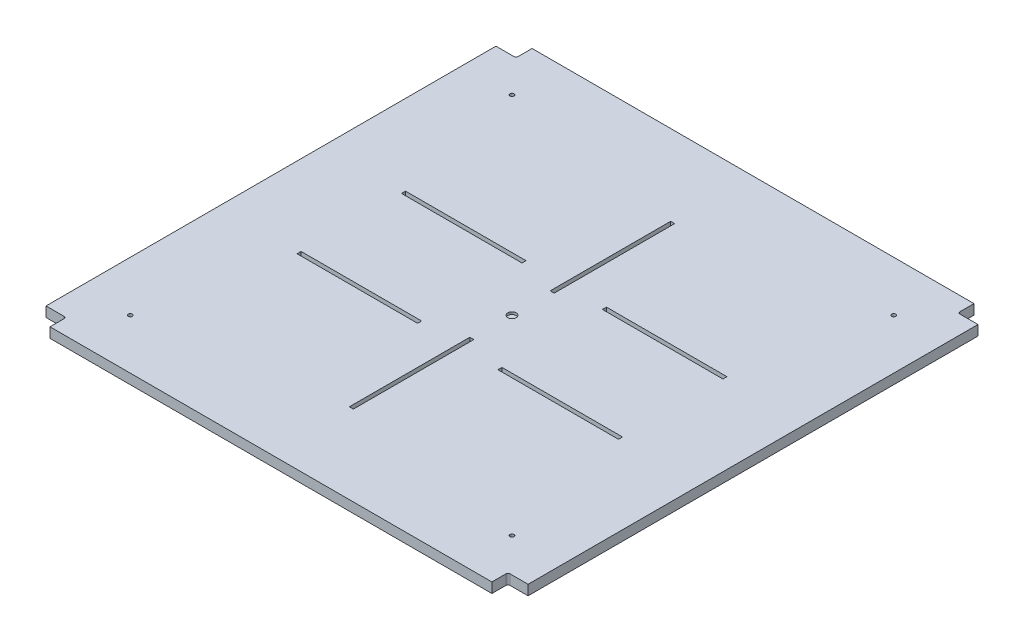
SolidWorks part; units mm, degrees
ref_plane "Спереди" through (0, 0, 0) normal (0, 0, 1) x (1, 0, 0)
ref_plane "Сверху" through (0, 0, 0) normal (0, 1, 0) x (1, 0, 0)
ref_plane "Справа" through (0, 0, 0) normal (1, 0, 0) x (0, 0, -1)
sketch "Эскиз1" plane through (0, 0, 0) normal (0, 1, 0) x (1, 0, 0)
  line L0 (-1200, 1120) -> (-1100, 1120)
  line L1 (-1200, -1200) -> (1200, -1200)
  line L2 (-1200, -1200) -> (-1200, 1200)
  line L3 (-1200, 1200) -> (1200, 1200)
  line L4 (1200, -1200) -> (1200, 1200)
  line L5 (-1200, -1200) -> (1200, 1200) construction
  line L6 (-1200, 1200) -> (1200, -1200) construction
  line L7 (-1100, 1120) -> (-1100, 1200)
  line L8 (0, 0) -> (1200, 0) construction
  line L9 (0, 0) -> (0, 1200) construction
  line L10 (1200, 1120) -> (1100, 1120)
  line L11 (1100, 1120) -> (1100, 1200)
  line L12 (1200, -1120) -> (1100, -1120)
  line L13 (1100, -1120) -> (1100, -1200)
  line L14 (-1200, -1120) -> (-1100, -1120)
  line L15 (-1100, -1120) -> (-1100, -1200)
  point P0 (0, 0)
  dimension "D1" = 2400
  dimension "D2" = 2400
  dimension "D3" = 80
  dimension "D4" = 100
extrude "Бобышка-Вытянуть1" add sketch "Эскиз1" along normal mid plane 50 contours L14 L15 L1 L13 L12 L4 L10 L11 L3 L7 L0 L2
fillet "Скругление1" radius 10 4 edges at (-1100, 0, -1120) (1100, 0, -1120) (1100, 0, 1120) (-1100, 0, 1120)
sketch "Эскиз2" plane through (0, 25, 0) normal (0, 1, 0) x (1, 0, 0)
  line L1 (-950, -950) -> (950, -950)
  line L2 (-950, -950) -> (-950, 950)
  line L3 (-950, 950) -> (950, 950)
  line L4 (950, -950) -> (950, 950)
  line L5 (-950, -950) -> (950, 950) construction
  line L6 (-950, 950) -> (950, -950) construction
  circle A0 centre (-950, 950) radius 10
  circle A1 centre (950, 950) radius 10
  circle A2 centre (950, -950) radius 10
  circle A3 centre (-950, -950) radius 10
  point P0 (0, 0)
  dimension "D2" = 20
  dimension "D1" = 1900
extrude "Вырез-Вытянуть1" cut sketch "Эскиз2" against normal through all contours A0 | A1 | A2 | A3
sketch "Эскиз3" plane through (0, 25, 0) normal (0, 1, 0) x (1, 0, 0)
  circle A0 centre (0, 0) radius 21
  dimension "D1" = 42
extrude "Вырез-Вытянуть2" cut sketch "Эскиз3" against normal blind 12
sketch "Эскиз4" plane through (0, 25, 0) normal (0, 1, 0) x (1, 0, 0)
  line L0 (0, 0) -> (1200, 0) construction
  line L1 (1200, -1120) -> (1200, 1120) construction
  line L2 (0, 0) -> (0, 1200) construction
  line L3 (-1100, 1200) -> (1100, 1200) construction
  line L4 (-10, -800) -> (10, -800)
  line L5 (-10, 200) -> (10, 200)
  line L6 (-10, 200) -> (-10, 800)
  line L7 (-10, 800) -> (10, 800)
  line L8 (10, 200) -> (10, 800)
  line L9 (-10, 200) -> (10, 800) construction
  line L10 (-10, 800) -> (10, 200) construction
  line L11 (-10, -200) -> (10, -200)
  line L12 (-10, -200) -> (-10, -800)
  line L13 (10, -200) -> (10, -800)
  line L14 (800, -250) -> (800, -270)
  line L15 (200, 250) -> (800, 250)
  line L16 (200, 250) -> (200, 270)
  line L17 (200, 270) -> (800, 270)
  line L18 (800, 250) -> (800, 270)
  line L19 (200, 250) -> (800, 270) construction
  line L20 (200, 270) -> (800, 250) construction
  line L21 (200, -250) -> (800, -250)
  line L22 (200, -250) -> (200, -270)
  line L23 (200, -270) -> (800, -270)
  line L24 (-200, -270) -> (-800, -270)
  line L25 (-200, -250) -> (-200, -270)
  line L26 (-200, -250) -> (-800, -250)
  line L27 (-800, -250) -> (-800, -270)
  line L28 (-200, 250) -> (-200, 270)
  line L29 (-200, 270) -> (-800, 270)
  line L30 (-800, 250) -> (-800, 270)
  line L31 (-200, 250) -> (-800, 250)
  point P5 (0, 500)
  point P17 (500, 260)
  dimension "D1" = 20
  dimension "D2" = 600
  dimension "D3" = 200
  dimension "D4" = 20
  dimension "D5" = 600
  dimension "D6" = 250
  dimension "D7" = 200
extrude "Вырез-Вытянуть3" cut sketch "Эскиз4" against normal through all
